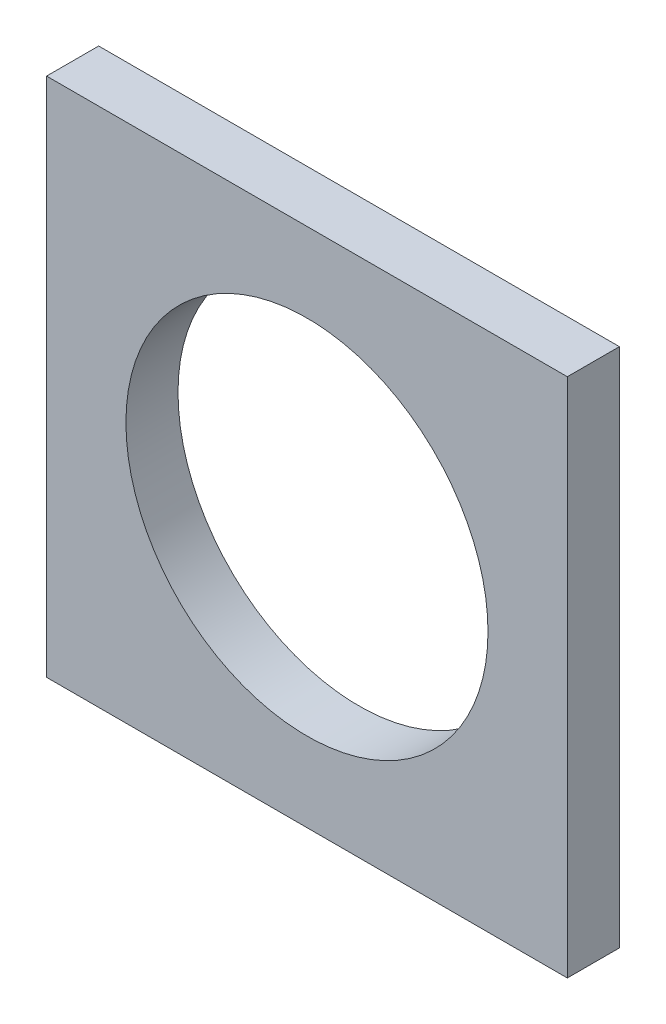
SolidWorks part; units mm, degrees
ref_plane "前视基准面" through (0, 0, 0) normal (0, 0, 1) x (1, 0, 0)
ref_plane "上视基准面" through (0, 0, 0) normal (0, 1, 0) x (1, 0, 0)
ref_plane "右视基准面" through (0, 0, 0) normal (1, 0, 0) x (0, 0, -1)
other "Configuration Table"
sketch "草图1" plane through (0, 0, 0) normal (0, 0, 1) x (1, 0, 0)
  line L1 (-50, -50) -> (50, -50)
  line L2 (-50, -50) -> (-50, 50)
  line L3 (-50, 50) -> (50, 50)
  line L4 (50, -50) -> (50, 50)
  line L5 (-50, -50) -> (50, 50) construction
  line L6 (-50, 50) -> (50, -50) construction
  circle A0 centre (0, 0) radius 34.7646
  point P0 (0, 0)
  dimension "D1" = 100
  dimension "D2" = 100
extrude "凸台-拉伸1" add sketch "草图1" along normal blind 10
